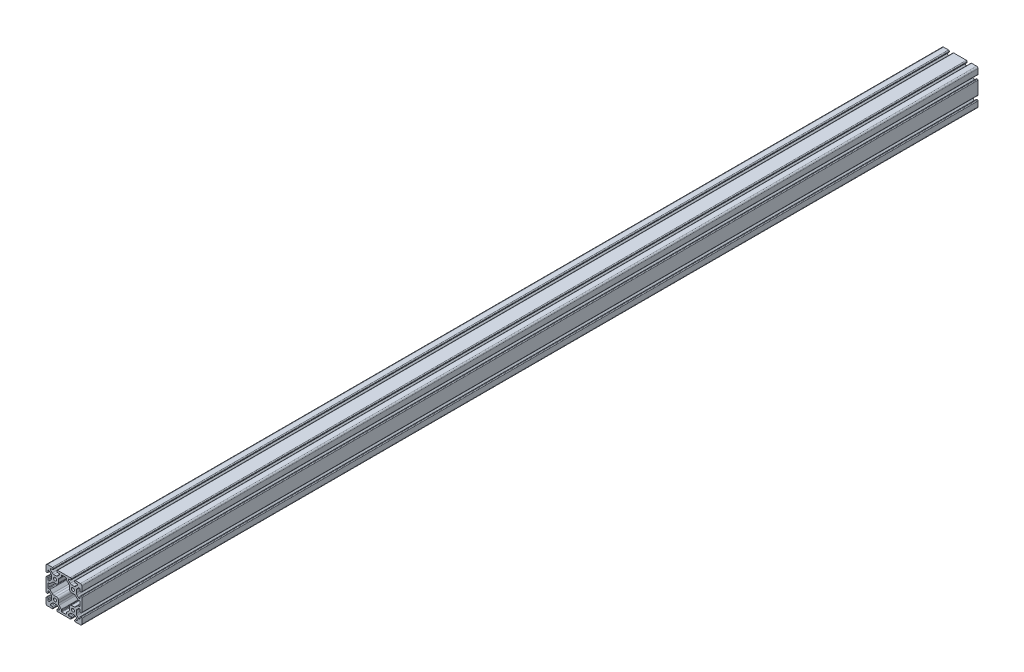
SolidWorks part; units mm, degrees
material "6061 Alloy"
ref_plane "Front Plane" through (0, 0, 0) normal (0, 0, 1) x (1, 0, 0)
ref_plane "Top Plane" through (0, 0, 0) normal (0, 1, 0) x (1, 0, 0)
ref_plane "Right Plane" through (0, 0, 0) normal (1, 0, 0) x (0, 0, -1)
sketch "Sketch1" plane through (0, 0, 0) normal (0, 0, 1) x (1, 0, 0)
  line L0 (0, -40) -> (0, 40) construction
  line L1 (0, 0) -> (-43.5804, 43.5804) construction
  line L2 (-20, 20) -> (-47.7323, 20) construction
  line L3 (-20, 20) -> (3.796, 43.796) construction
  line L4 (-20, 20) -> (-20, 43.5758) construction
  line L5 (-20, -27.7) -> (-20, -47.5576) construction
  line L131 (29.0912, 26.0365) -> (33.0827, 30.028)
  line L132 (27.7, 17.3222) -> (27.7, 22.6778)
  line L133 (29.0912, 13.9635) -> (33.0827, 9.972)
  line L134 (33.6201, 9.7494) -> (34.11, 9.7494)
  line L135 (35.68, 11.3194) -> (35.68, 14.2221)
  line L136 (37.25, 15.7921) -> (38.43, 15.7921)
  line L137 (40, 14.2221) -> (40, 7.0214)
  line L138 (40, 7.0214) -> (40, -7.0214)
  line L139 (40, -7.0214) -> (40, -14.2221)
  line L140 (38.43, -15.7921) -> (37.25, -15.7921)
  line L141 (35.68, -14.2221) -> (35.68, -11.3194)
  line L142 (33.6201, -9.7494) -> (34.11, -9.7494)
  line L143 (29.0912, -13.9635) -> (33.0827, -9.972)
  line L144 (27.7, -22.6778) -> (27.7, -17.3222)
  line L145 (29.0912, -26.0365) -> (33.0827, -30.028)
  line L146 (33.6201, -30.2506) -> (34.11, -30.2506)
  line L147 (35.68, -28.6806) -> (35.68, -25.7779)
  line L148 (37.25, -24.2079) -> (38.43, -24.2079)
  line L149 (40, -25.7779) -> (40, -33.0259)
  line L150 (40, -33.0259) -> (40, -36.83)
  line L151 (36.83, -40) -> (32.9998, -40)
  line L152 (32.9998, -40) -> (25.5696, -40)
  line L153 (23.9996, -38.43) -> (23.9996, -37.25)
  line L154 (25.5696, -35.68) -> (28.4723, -35.68)
  line L155 (30.0413, -34.0552) -> (30.0171, -33.3605)
  line L156 (29.7949, -32.8496) -> (26.0365, -29.0912)
  line L157 (17.3222, -27.7) -> (22.6778, -27.7)
  line L158 (10.035, -33.0197) -> (13.9635, -29.0912)
  line L159 (9.8124, -33.8926) -> (9.8124, -33.5571)
  line L160 (11.3824, -35.4626) -> (14.4246, -35.4626)
  line L161 (15.9946, -37.0326) -> (15.9946, -38.43)
  line L162 (14.4246, -40) -> (6.9987, -40)
  line L163 (6.9987, -40) -> (-6.9987, -40)
  line L164 (-6.9987, -40) -> (-14.4292, -40)
  line L165 (-15.9992, -38.43) -> (-15.9992, -37.25)
  line L166 (-14.4292, -35.68) -> (-11.5265, -35.68)
  line L167 (-9.9574, -34.0552) -> (-9.9816, -33.3618)
  line L168 (-10.2038, -32.8509) -> (-13.9635, -29.0912)
  line L169 (-22.6778, -27.7) -> (-17.3222, -27.7)
  line L170 (-30.028, -33.0827) -> (-26.0365, -29.0912)
  line L171 (-30.2506, -34.11) -> (-30.2506, -33.6201)
  line L172 (-28.6806, -35.68) -> (-25.7231, -35.68)
  line L173 (-24.1531, -37.25) -> (-24.1531, -38.43)
  line L174 (-25.7231, -40) -> (-33, -40)
  line L175 (-33, -40) -> (-36.83, -40)
  line L176 (-40, -36.83) -> (-40, -33.0191)
  line L177 (-40, -33.0191) -> (-40, -25.591)
  line L178 (-38.43, -24.021) -> (-37.25, -24.021)
  line L179 (-35.68, -28.4937) -> (-35.68, -25.591)
  line L180 (-34.0552, -30.0627) -> (-33.3827, -30.0392)
  line L181 (-32.8718, -29.8171) -> (-29.0912, -26.0365)
  line L182 (-27.7, -22.6778) -> (-27.7, -17.3222)
  line L183 (-29.0912, -13.9635) -> (-33.0827, -9.972)
  line L184 (-34.11, -9.7494) -> (-33.6201, -9.7494)
  line L185 (-35.68, -11.3194) -> (-35.68, -14.4473)
  line L186 (-38.43, -16.0173) -> (-37.25, -16.0173)
  line L187 (-40, -14.4473) -> (-40, -7.0169)
  line L188 (-40, -7.0169) -> (-40, 7.0169)
  line L189 (-40, 7.0169) -> (-40, 14.1348)
  line L190 (-38.1948, 15.94) -> (-36.9772, 15.94)
  line L191 (-35.68, 11.3194) -> (-35.68, 14.6428)
  line L192 (-34.11, 9.7494) -> (-33.6201, 9.7494)
  line L193 (-33.0827, 9.972) -> (-29.0912, 13.9635)
  line L194 (-27.7, 17.3222) -> (-27.7, 22.6778)
  line L195 (-29.0912, 26.0365) -> (-33.0827, 30.028)
  line L196 (-34.11, 30.2506) -> (-33.6201, 30.2506)
  line L197 (-35.68, 28.6806) -> (-35.68, 25.3572)
  line L198 (-38.1948, 24.06) -> (-36.9772, 24.06)
  line L199 (-40, 25.8652) -> (-40, 33.3181)
  line L200 (-40, 33.3181) -> (-40, 36.83)
  line L201 (-36.83, 40) -> (-33.0314, 40)
  line L202 (-33.0314, 40) -> (-25.8652, 40)
  line L203 (-24.06, 36.9772) -> (-24.06, 38.1948)
  line L204 (-25.3572, 35.68) -> (-28.7018, 35.68)
  line L205 (-30.285, 33.6069) -> (-30.285, 34.0968)
  line L206 (-30.0961, 33.1508) -> (-26.0365, 29.0912)
  line L207 (-22.6778, 27.7) -> (-17.3222, 27.7)
  line L208 (-13.9635, 29.0912) -> (-9.9039, 33.1508)
  line L209 (-9.715, 33.6069) -> (-9.715, 34.0968)
  line L210 (-14.6428, 35.68) -> (-11.2982, 35.68)
  line L211 (-15.94, 36.9772) -> (-15.94, 38.1948)
  line L212 (-14.1348, 40) -> (-6.9844, 40)
  line L213 (-6.9844, 40) -> (6.9844, 40)
  line L214 (6.9844, 40) -> (14.1348, 40)
  line L215 (15.94, 36.9772) -> (15.94, 38.1948)
  line L216 (14.6428, 35.68) -> (11.2982, 35.68)
  line L217 (9.715, 33.6069) -> (9.715, 34.0968)
  line L218 (9.9039, 33.1508) -> (13.9635, 29.0912)
  line L219 (17.3222, 27.7) -> (22.6778, 27.7)
  line L220 (26.0365, 29.0912) -> (30.028, 33.0827)
  line L221 (30.2506, 33.6201) -> (30.2506, 34.11)
  line L222 (25.5409, 35.679) -> (28.6258, 35.679)
  line L223 (23.9709, 37.249) -> (23.9709, 38.43)
  line L224 (25.5409, 40) -> (36.83, 40)
  line L226 (40, 36.83) -> (40, 32.9339)
  line L227 (40, 32.9339) -> (40, 25.7779)
  line L228 (38.43, 24.2079) -> (37.0956, 24.2079)
  line L229 (35.5256, 25.7779) -> (35.5256, 28.6806)
  line L230 (33.6201, 30.2506) -> (33.9556, 30.2506)
  line L231 (17.07, 12.32) -> (22.6578, 12.32)
  line L232 (26.0165, 10.9288) -> (31.1439, 5.8014)
  line L233 (32.0419, 5.4294) -> (34.41, 5.4294)
  line L234 (35.68, -4.1594) -> (35.68, 4.1594)
  line L235 (32.0419, -5.4294) -> (34.41, -5.4294)
  line L236 (26.0165, -10.9288) -> (31.1439, -5.8014)
  line L237 (17.07, -12.32) -> (22.6578, -12.32)
  line L238 (12.32, -22.6578) -> (12.32, -17.07)
  line L239 (5.8014, -31.1439) -> (10.9288, -26.0165)
  line L240 (5.4294, -34.41) -> (5.4294, -32.0419)
  line L241 (-4.1594, -35.68) -> (4.1594, -35.68)
  line L242 (-5.4294, -34.41) -> (-5.4294, -32.0419)
  line L243 (-5.8014, -31.1439) -> (-10.9288, -26.0165)
  line L244 (-12.32, -22.6578) -> (-12.32, -17.07)
  line L245 (-22.6578, -12.32) -> (-17.07, -12.32)
  line L246 (-26.0165, -10.9288) -> (-31.1439, -5.8014)
  line L247 (-34.41, -5.4294) -> (-32.0419, -5.4294)
  line L248 (-35.68, -4.1594) -> (-35.68, 4.1594)
  line L249 (-34.41, 5.4294) -> (-32.0419, 5.4294)
  line L250 (-31.1439, 5.8014) -> (-26.0165, 10.9288)
  line L251 (-22.6578, 12.32) -> (-17.07, 12.32)
  line L252 (-12.32, 17.07) -> (-12.32, 22.6578)
  line L253 (-10.9288, 26.0165) -> (-5.8014, 31.1439)
  line L254 (-5.4294, 32.0419) -> (-5.4294, 34.41)
  line L255 (-4.1594, 35.68) -> (4.1594, 35.68)
  line L256 (5.4294, 32.0419) -> (5.4294, 34.41)
  line L257 (5.8014, 31.1439) -> (10.9288, 26.0165)
  line L258 (12.32, 17.07) -> (12.32, 22.6578)
  line L260 (-40, 0) -> (40, 0) construction
  circle A116 centre (-20, 20) radius 3.4
  circle A117 centre (20, 20) radius 3.4
  circle A118 centre (20, -20) radius 3.4
  circle A119 centre (-20, -20) radius 3.4
  arc A120 (29.0912, 26.0365) -> (27.7, 22.6778) centre (32.45, 22.6778) ccw
  arc A121 (27.7, 17.3222) -> (29.0912, 13.9635) centre (32.45, 17.3222) ccw
  arc A122 (33.0827, 9.972) -> (33.6201, 9.7494) centre (33.6201, 10.5094) ccw
  arc A123 (34.11, 9.7494) -> (35.68, 11.3194) centre (34.11, 11.3194) ccw
  arc A124 (37.25, 15.7921) -> (35.68, 14.2221) centre (37.25, 14.2221) ccw
  arc A125 (40, 14.2221) -> (38.43, 15.7921) centre (38.43, 14.2221) ccw
  arc A126 (38.43, -15.7921) -> (40, -14.2221) centre (38.43, -14.2221) ccw
  arc A127 (35.68, -14.2221) -> (37.25, -15.7921) centre (37.25, -14.2221) ccw
  arc A128 (35.68, -11.3194) -> (34.11, -9.7494) centre (34.11, -11.3194) ccw
  arc A129 (33.6201, -9.7494) -> (33.0827, -9.972) centre (33.6201, -10.5094) ccw
  arc A130 (29.0912, -13.9635) -> (27.7, -17.3222) centre (32.45, -17.3222) ccw
  arc A131 (27.7, -22.6778) -> (29.0912, -26.0365) centre (32.45, -22.6778) ccw
  arc A132 (33.0827, -30.028) -> (33.6201, -30.2506) centre (33.6201, -29.4906) ccw
  arc A133 (34.11, -30.2506) -> (35.68, -28.6806) centre (34.11, -28.6806) ccw
  arc A134 (37.25, -24.2079) -> (35.68, -25.7779) centre (37.25, -25.7779) ccw
  arc A135 (40, -25.7779) -> (38.43, -24.2079) centre (38.43, -25.7779) ccw
  arc A136 (36.83, -40) -> (40, -36.83) centre (36.83, -36.83) ccw
  arc A137 (23.9996, -38.43) -> (25.5696, -40) centre (25.5696, -38.43) ccw
  arc A138 (25.5696, -35.68) -> (23.9996, -37.25) centre (25.5696, -37.25) ccw
  arc A139 (28.4723, -35.68) -> (30.0413, -34.0552) centre (28.4723, -34.11) ccw
  arc A140 (30.0171, -33.3605) -> (29.7949, -32.8496) centre (29.2575, -33.387) ccw
  arc A141 (26.0365, -29.0912) -> (22.6778, -27.7) centre (22.6778, -32.45) ccw
  arc A142 (17.3222, -27.7) -> (13.9635, -29.0912) centre (17.3222, -32.45) ccw
  arc A143 (10.035, -33.0197) -> (9.8124, -33.5571) centre (10.5724, -33.5571) ccw
  arc A144 (9.8124, -33.8926) -> (11.3824, -35.4626) centre (11.3824, -33.8926) ccw
  arc A145 (15.9946, -37.0326) -> (14.4246, -35.4626) centre (14.4246, -37.0326) ccw
  arc A146 (14.4246, -40) -> (15.9946, -38.43) centre (14.4246, -38.43) ccw
  arc A147 (-15.9992, -38.43) -> (-14.4292, -40) centre (-14.4292, -38.43) ccw
  arc A148 (-14.4292, -35.68) -> (-15.9992, -37.25) centre (-14.4292, -37.25) ccw
  arc A149 (-11.5265, -35.68) -> (-9.9574, -34.0552) centre (-11.5265, -34.11) ccw
  arc A150 (-9.9816, -33.3618) -> (-10.2038, -32.8509) centre (-10.7412, -33.3883) ccw
  arc A151 (-13.9635, -29.0912) -> (-17.3222, -27.7) centre (-17.3222, -32.45) ccw
  arc A152 (-22.6778, -27.7) -> (-26.0365, -29.0912) centre (-22.6778, -32.45) ccw
  arc A153 (-30.028, -33.0827) -> (-30.2506, -33.6201) centre (-29.4906, -33.6201) ccw
  arc A154 (-30.2506, -34.11) -> (-28.6806, -35.68) centre (-28.6806, -34.11) ccw
  arc A155 (-24.1531, -37.25) -> (-25.7231, -35.68) centre (-25.7231, -37.25) ccw
  arc A156 (-25.7231, -40) -> (-24.1531, -38.43) centre (-25.7231, -38.43) ccw
  arc A157 (-40, -36.83) -> (-36.83, -40) centre (-36.83, -36.83) ccw
  arc A158 (-38.43, -24.021) -> (-40, -25.591) centre (-38.43, -25.591) ccw
  arc A159 (-35.68, -25.591) -> (-37.25, -24.021) centre (-37.25, -25.591) ccw
  arc A160 (-35.68, -28.4937) -> (-34.0552, -30.0627) centre (-34.11, -28.4937) ccw
  arc A161 (-33.3827, -30.0392) -> (-32.8718, -29.8171) centre (-33.4092, -29.2797) ccw
  arc A162 (-29.0912, -26.0365) -> (-27.7, -22.6778) centre (-32.45, -22.6778) ccw
  arc A163 (-27.7, -17.3222) -> (-29.0912, -13.9635) centre (-32.45, -17.3222) ccw
  arc A164 (-33.0827, -9.972) -> (-33.6201, -9.7494) centre (-33.6201, -10.5094) ccw
  arc A165 (-34.11, -9.7494) -> (-35.68, -11.3194) centre (-34.11, -11.3194) ccw
  arc A166 (-37.25, -16.0173) -> (-35.68, -14.4473) centre (-37.25, -14.4473) ccw
  arc A167 (-40, -14.4473) -> (-38.43, -16.0173) centre (-38.43, -14.4473) ccw
  arc A168 (-38.1948, 15.94) -> (-40, 14.1348) centre (-38.1948, 14.1348) ccw
  arc A169 (-35.68, 14.6428) -> (-36.9772, 15.94) centre (-36.9772, 14.6428) ccw
  arc A170 (-35.68, 11.3194) -> (-34.11, 9.7494) centre (-34.11, 11.3194) ccw
  arc A171 (-33.6201, 9.7494) -> (-33.0827, 9.972) centre (-33.6201, 10.5094) ccw
  arc A172 (-29.0912, 13.9635) -> (-27.7, 17.3222) centre (-32.45, 17.3222) ccw
  arc A173 (-27.7, 22.6778) -> (-29.0912, 26.0365) centre (-32.45, 22.6778) ccw
  arc A174 (-33.0827, 30.028) -> (-33.6201, 30.2506) centre (-33.6201, 29.4906) ccw
  arc A175 (-34.11, 30.2506) -> (-35.68, 28.6806) centre (-34.11, 28.6806) ccw
  arc A176 (-36.9772, 24.06) -> (-35.68, 25.3572) centre (-36.9772, 25.3572) ccw
  arc A177 (-40, 25.8652) -> (-38.1948, 24.06) centre (-38.1948, 25.8652) ccw
  arc A178 (-36.83, 40) -> (-40, 36.83) centre (-36.83, 36.83) ccw
  arc A179 (-24.06, 38.1948) -> (-25.8652, 40) centre (-25.8652, 38.1948) ccw
  arc A180 (-25.3572, 35.68) -> (-24.06, 36.9772) centre (-25.3572, 36.9772) ccw
  arc A181 (-28.7018, 35.68) -> (-30.285, 34.0968) centre (-28.7018, 34.0968) ccw
  arc A182 (-30.285, 33.6069) -> (-30.0961, 33.1508) centre (-29.6399, 33.6069) ccw
  arc A183 (-26.0365, 29.0912) -> (-22.6778, 27.7) centre (-22.6778, 32.45) ccw
  arc A184 (-17.3222, 27.7) -> (-13.9635, 29.0912) centre (-17.3222, 32.45) ccw
  arc A185 (-9.9039, 33.1508) -> (-9.715, 33.6069) centre (-10.3601, 33.6069) ccw
  arc A186 (-9.715, 34.0968) -> (-11.2982, 35.68) centre (-11.2982, 34.0968) ccw
  arc A187 (-15.94, 36.9772) -> (-14.6428, 35.68) centre (-14.6428, 36.9772) ccw
  arc A188 (-14.1348, 40) -> (-15.94, 38.1948) centre (-14.1348, 38.1948) ccw
  arc A189 (15.94, 38.1948) -> (14.1348, 40) centre (14.1348, 38.1948) ccw
  arc A190 (14.6428, 35.68) -> (15.94, 36.9772) centre (14.6428, 36.9772) ccw
  arc A191 (11.2982, 35.68) -> (9.715, 34.0968) centre (11.2982, 34.0968) ccw
  arc A192 (9.715, 33.6069) -> (9.9039, 33.1508) centre (10.3601, 33.6069) ccw
  arc A193 (13.9635, 29.0912) -> (17.3222, 27.7) centre (17.3222, 32.45) ccw
  arc A194 (22.6778, 27.7) -> (26.0365, 29.0912) centre (22.6778, 32.45) ccw
  arc A195 (30.028, 33.0827) -> (30.2506, 33.6201) centre (29.4906, 33.6201) ccw
  arc A196 (30.2506, 34.11) -> (28.6258, 35.679) centre (28.6806, 34.11) ccw
  arc A197 (23.9709, 37.249) -> (25.5409, 35.679) centre (25.5409, 37.249) ccw
  arc A198 (25.5409, 40) -> (23.9709, 38.43) centre (25.5409, 38.43) ccw
  arc A199 (40, 36.83) -> (36.83, 40) centre (36.83, 36.83) ccw
  arc A200 (38.43, 24.2079) -> (40, 25.7779) centre (38.43, 25.7779) ccw
  arc A201 (35.5256, 25.7779) -> (37.0956, 24.2079) centre (37.0956, 25.7779) ccw
  arc A202 (35.5256, 28.6806) -> (33.9556, 30.2506) centre (33.9556, 28.6806) ccw
  arc A203 (33.6201, 30.2506) -> (33.0827, 30.028) centre (33.6201, 29.4906) ccw
  arc A204 (26.0165, 10.9288) -> (22.6578, 12.32) centre (22.6578, 7.57) ccw
  arc A205 (31.1439, 5.8014) -> (32.0419, 5.4294) centre (32.0419, 6.6994) ccw
  arc A206 (35.68, 4.1594) -> (34.41, 5.4294) centre (34.41, 4.1594) ccw
  arc A207 (34.41, -5.4294) -> (35.68, -4.1594) centre (34.41, -4.1594) ccw
  arc A208 (32.0419, -5.4294) -> (31.1439, -5.8014) centre (32.0419, -6.6994) ccw
  arc A209 (22.6578, -12.32) -> (26.0165, -10.9288) centre (22.6578, -7.57) ccw
  arc A210 (17.07, -12.32) -> (12.32, -17.07) centre (17.07, -17.07) ccw
  arc A211 (10.9288, -26.0165) -> (12.32, -22.6578) centre (7.57, -22.6578) ccw
  arc A212 (5.8014, -31.1439) -> (5.4294, -32.0419) centre (6.6994, -32.0419) ccw
  arc A213 (4.1594, -35.68) -> (5.4294, -34.41) centre (4.1594, -34.41) ccw
  arc A214 (-5.4294, -34.41) -> (-4.1594, -35.68) centre (-4.1594, -34.41) ccw
  arc A215 (-5.4294, -32.0419) -> (-5.8014, -31.1439) centre (-6.6994, -32.0419) ccw
  arc A216 (-12.32, -22.6578) -> (-10.9288, -26.0165) centre (-7.57, -22.6578) ccw
  arc A217 (-12.32, -17.07) -> (-17.07, -12.32) centre (-17.07, -17.07) ccw
  arc A218 (-26.0165, -10.9288) -> (-22.6578, -12.32) centre (-22.6578, -7.57) ccw
  arc A219 (-31.1439, -5.8014) -> (-32.0419, -5.4294) centre (-32.0419, -6.6994) ccw
  arc A220 (-35.68, -4.1594) -> (-34.41, -5.4294) centre (-34.41, -4.1594) ccw
  arc A221 (-34.41, 5.4294) -> (-35.68, 4.1594) centre (-34.41, 4.1594) ccw
  arc A222 (-32.0419, 5.4294) -> (-31.1439, 5.8014) centre (-32.0419, 6.6994) ccw
  arc A223 (-22.6578, 12.32) -> (-26.0165, 10.9288) centre (-22.6578, 7.57) ccw
  arc A224 (-17.07, 12.32) -> (-12.32, 17.07) centre (-17.07, 17.07) ccw
  arc A225 (-10.9288, 26.0165) -> (-12.32, 22.6578) centre (-7.57, 22.6578) ccw
  arc A226 (-5.8014, 31.1439) -> (-5.4294, 32.0419) centre (-6.6994, 32.0419) ccw
  arc A227 (-4.1594, 35.68) -> (-5.4294, 34.41) centre (-4.1594, 34.41) ccw
  arc A228 (5.4294, 34.41) -> (4.1594, 35.68) centre (4.1594, 34.41) ccw
  arc A229 (5.4294, 32.0419) -> (5.8014, 31.1439) centre (6.6994, 32.0419) ccw
  arc A230 (12.32, 22.6578) -> (10.9288, 26.0165) centre (7.57, 22.6578) ccw
  arc A231 (12.32, 17.07) -> (17.07, 12.32) centre (17.07, 17.07) ccw
  dimension "D8" = 6.8
  dimension "D1" = 80
  dimension "D2" = 40
  dimension "D3" = 20
  dimension "D4" = 20.57
  dimension "D5" = 4.32
  dimension "D6" = 4.32
  dimension "D7" = 8.12
  dimension "D9" = 4.32
  dimension "D10" = 12.3
extrude "Extrude1" add sketch "Sketch1" against normal blind 2000
